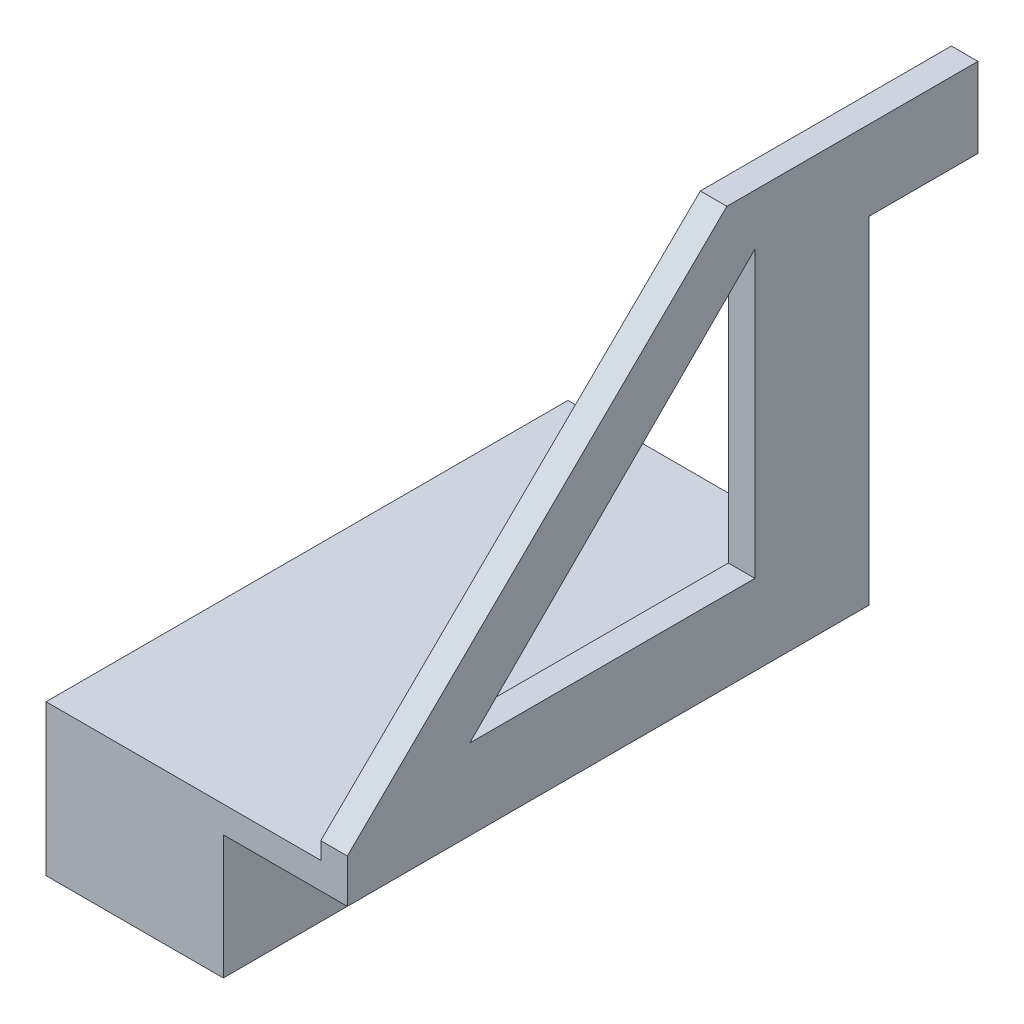
SolidWorks part; units mm, degrees
ref_plane "前视基准面" through (0, 0, 0) normal (0, 0, 1) x (1, 0, 0)
ref_plane "上视基准面" through (0, 0, 0) normal (0, 1, 0) x (1, 0, 0)
ref_plane "右视基准面" through (0, 0, 0) normal (1, 0, 0) x (0, 0, -1)
sketch "草图2" plane through (0, 0, 0) normal (0, 1, 0) x (1, 0, 0)
  line L1 (0, 0) -> (17, 0)
  line L2 (0, 0) -> (0, 35)
  line L3 (0, 35) -> (17, 35)
  line L4 (17, 0) -> (17, 35)
  dimension "D1" = 17
  dimension "D2" = 35
extrude "凸台-拉伸1" add sketch "草图2" along normal blind 1.5
sketch "草图3" plane through (0, 0, 0) normal (0, -1, 0) x (1, 0, 0)
  line L0 (17, -35) -> (0, -35) construction
  line L1 (0, 0) -> (10, 0)
  line L2 (0, 0) -> (0, -35)
  line L3 (0, -35) -> (10, -35)
  line L4 (10, 0) -> (10, -35)
  dimension "D1" = 10
extrude "凸台-拉伸2" add sketch "草图3" along normal blind 7
sketch "草图4" plane through (0, 1.5, 0) normal (0, 1, 0) x (1, 0, 0)
  line L1 (17, 0) -> (15.5, 0)
  line L2 (17, 0) -> (17, 35.5777)
  line L3 (17, 35.5777) -> (15.5, 35.5777)
  line L4 (15.5, 0) -> (15.5, 35.5777)
  dimension "D1" = 1.5
extrude "凸台-拉伸3" add sketch "草图4" along normal blind 22
sketch "草图7" plane through (17, 0, 0) normal (1, 0, 0) x (0, 0, -1)
  line L0 (0, 23.5) -> (0, 2.4605)
  line L1 (0, 23.5) -> (0, 0) construction
  line L2 (0, 2.4605) -> (21.4133, 23.5)
  line L3 (0, 23.5) -> (35.5777, 23.5) construction
  line L4 (0, 23.5) -> (21.4133, 23.5)
  dimension "D1" = 21.0395
  dimension "D2" = 21.4133
extrude "切除-拉伸1" cut sketch "草图7" against normal up to next
sketch "草图8" plane through (17, 0, 0) normal (1, 0, 0) x (0, 0, -1)
  line L0 (22.9947, 20.6183) -> (6.9055, 4.529)
  line L1 (6.9055, 4.529) -> (22.9947, 4.529)
  line L2 (22.9947, 20.6183) -> (22.9947, 4.529)
  line L3 (35.5777, 23.5) -> (35.5777, 1.5) construction
  line L4 (35, 0) -> (0, 0) construction
  line L5 (0, 2.4605) -> (21.4133, 23.5) construction
  dimension "D1" = 12.583
  dimension "D2" = 16.0892
  dimension "D3" = 4.529
  dimension "D4" = 0.505
extrude "切除-拉伸2" cut sketch "草图8" against normal up to next
sketch "草图11" plane through (0, -7, 0) normal (0, -1, 0) x (1, 0, 0)
  line L0 (17, 0) -> (17, -35) construction
  line L1 (0, -36.2917) -> (17, -36.2917)
  line L2 (0, -36.2917) -> (0, -29.4448)
  line L3 (0, -29.4448) -> (17, -29.4448)
  line L4 (17, -36.2917) -> (17, -29.4448)
  line L5 (0, -35) -> (10, -35) construction
  dimension "D1" = 5.5552
  dimension "D2" = 6.8469
  dimension "D3" = 17
extrude "切除-拉伸7" cut sketch "草图11" against normal blind 26
